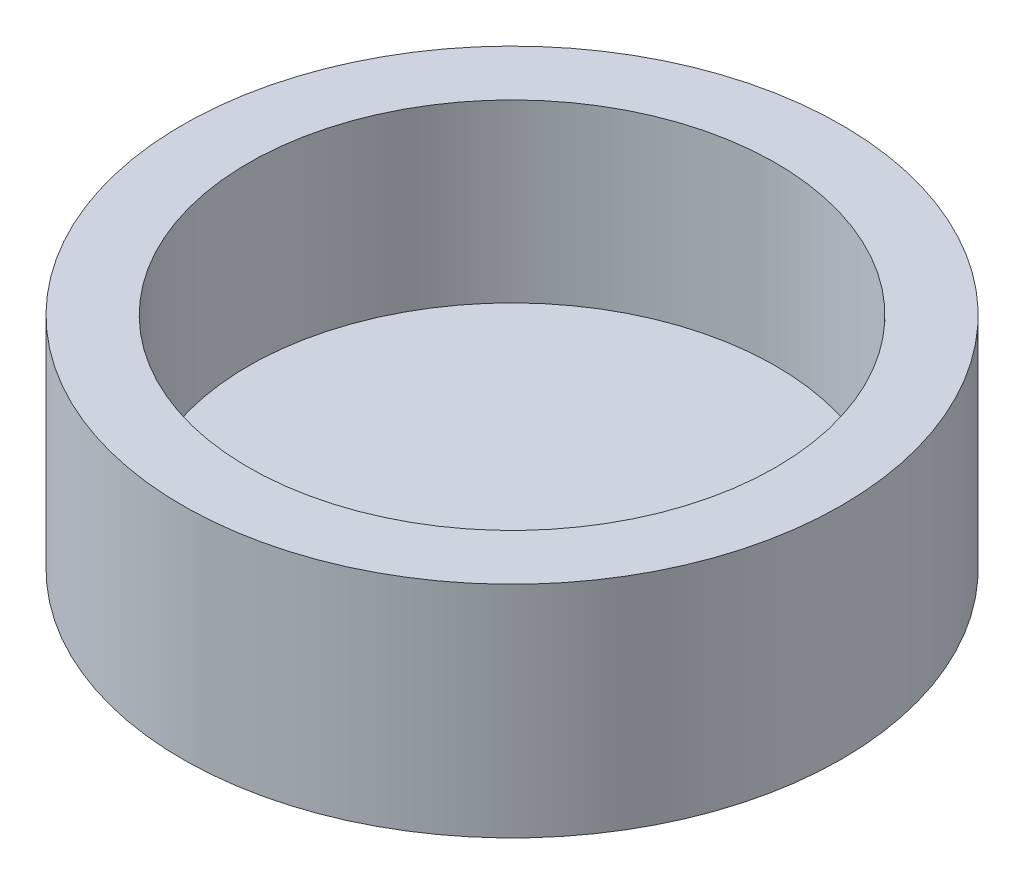
SolidWorks part; units mm, degrees
ref_plane "Front Plane" through (0, 0, 0) normal (0, 0, 1) x (1, 0, 0)
ref_plane "Top Plane" through (0, 0, 0) normal (0, 1, 0) x (1, 0, 0)
ref_plane "Right Plane" through (0, 0, 0) normal (1, 0, 0) x (0, 0, -1)
sketch "Sketch1" plane through (0, 0, 0) normal (0, 0, 1) x (1, 0, 0)
  line L0 (0, -99.7036) -> (0, 4885.4772) construction
  line L1 (0, 0) -> (6, 0)
  line L2 (6, 0) -> (6, 4)
  line L3 (6, 4) -> (7.5, 4)
  line L4 (7.5, 4) -> (7.5, -1)
  line L5 (7.5, -1) -> (0, -1)
  line L6 (0, -1) -> (0, 0)
  dimension "D1" = 1
  dimension "D2" = 6
  dimension "D3" = 7.5
  dimension "D4" = 4
revolve "Revolve1" add sketch "Sketch1" angle 360 about L0
